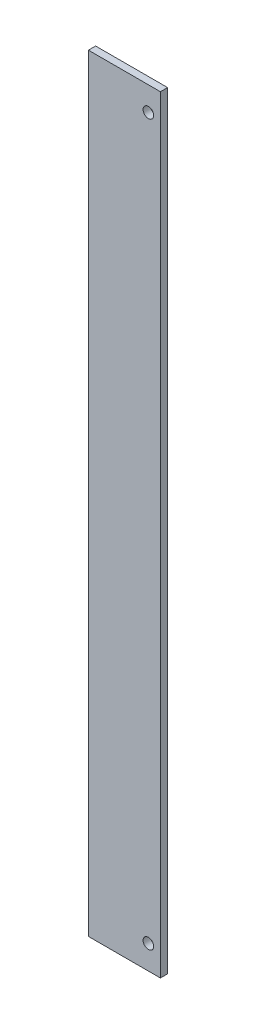
SolidWorks part; units mm, degrees
ref_plane "Plan de face" through (0, 0, 0) normal (0, 0, 1) x (1, 0, 0)
ref_plane "Plan de dessus" through (0, 0, 0) normal (0, 1, 0) x (1, 0, 0)
ref_plane "Plan de droite" through (0, 0, 0) normal (1, 0, 0) x (0, 0, -1)
sketch "Esquisse1" plane through (0, 0, 0) normal (0, 0, 1) x (1, 0, 0)
  line L0 (0, 0) -> (95, 0) construction
  line L1 (0, 0) -> (65, 0) construction
  line L2 (65, 0) -> (65, 165) construction
  line L3 (65, 165) -> (95, 165)
  line L4 (95, 165) -> (95, -155)
  line L5 (95, -155) -> (65, -155)
  line L7 (65, 165) -> (65, -155)
  dimension "D1" = 165
  dimension "D2" = 95
  dimension "D3" = 30
  dimension "D4" = 320
  dimension "D5" = 320
extrude "Boss.-Extru.1" add sketch "Esquisse1" along normal blind 3
sketch "Esquisse2" plane through (0, 0, 3) normal (0, 0, 1) x (1, 0, 0)
  line L0 (95, -155) -> (90, -155) construction
  line L1 (90, -155) -> (90, -145) construction
  line L2 (95, 165) -> (90, 165) construction
  line L3 (95, 165) -> (65, 165) construction
  line L4 (90, 165) -> (90, 155) construction
  circle A0 centre (90, -145) radius 2.2
  circle A1 centre (90, 155) radius 2.2
  dimension "D2" = 10
  dimension "D1" = 5
  dimension "D3" = 10
  dimension "D4" = 5
extrude "Enlèv. mat.-Extru.1" cut sketch "Esquisse2" against normal up to next
